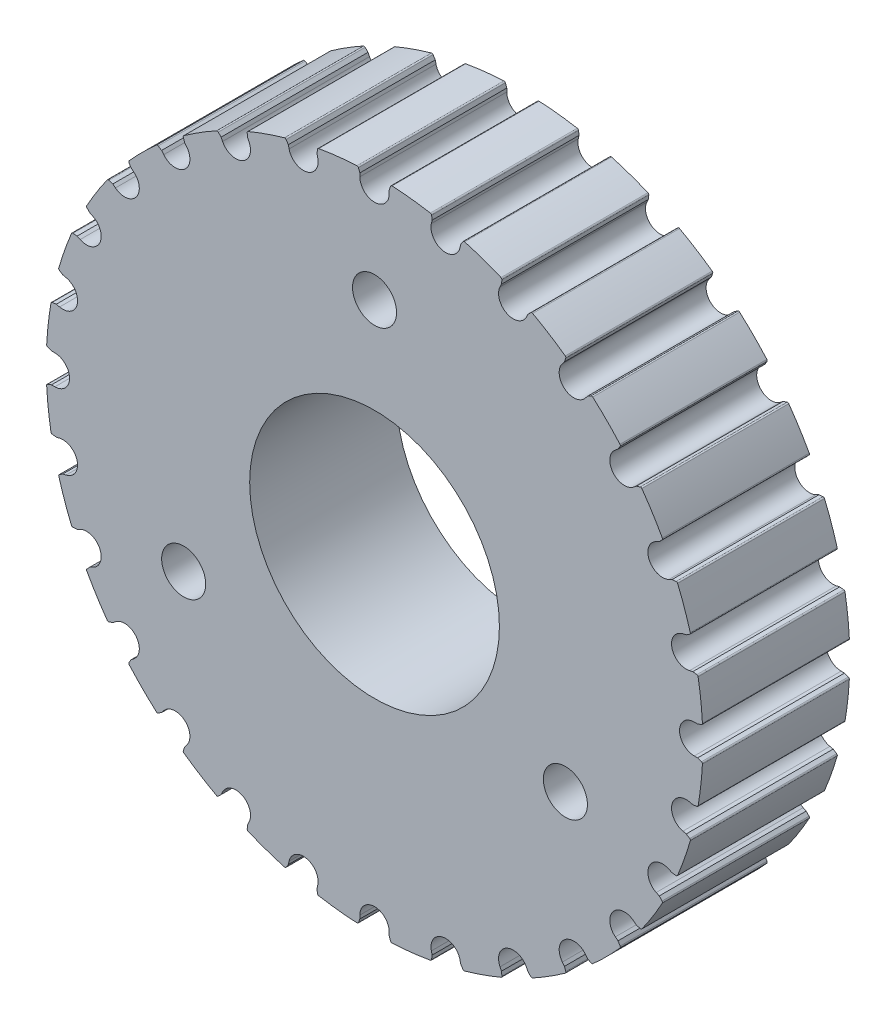
SolidWorks part; units mm, degrees
ref_plane "Спереди" through (0, 0, 0) normal (0, 0, 1) x (1, 0, 0)
ref_plane "Сверху" through (0, 0, 0) normal (0, 1, 0) x (1, 0, 0)
ref_plane "Справа" through (0, 0, 0) normal (1, 0, 0) x (0, 0, -1)
sketch "Эскиз1" plane through (0, 0, 0) normal (0, 0, 1) x (1, 0, 0)
  line L0 (0, 0) -> (0, 13.132) construction
  line L1 (-0.676, 21.1) -> (0, 21.1)
  line L2 (0, 21.1) -> (0.676, 21.1)
  line L3 (-0.676, 21.1) -> (-1.1207, 22.3219)
  line L4 (4.0361, 20.7214) -> (4.6952, 20.571)
  line L5 (4.6952, 20.571) -> (5.3542, 20.4206)
  line L6 (1.1207, 22.3219) -> (0.676, 21.1)
  line L7 (4.0361, 20.7214) -> (3.8745, 22.0116)
  line L8 (6.0597, 21.5128) -> (5.3542, 20.4206)
  line L9 (8.5459, 19.3037) -> (9.1549, 19.0104)
  line L10 (9.1549, 19.0104) -> (9.764, 18.7171)
  line L11 (8.5459, 19.3037) -> (8.6754, 20.5976)
  line L12 (10.6948, 19.6251) -> (9.764, 18.7171)
  line L13 (12.6271, 16.9181) -> (13.1556, 16.4966)
  line L14 (13.1556, 16.4966) -> (13.6842, 16.0752)
  line L15 (12.6271, 16.9181) -> (13.0412, 18.1507)
  line L16 (14.7937, 16.7532) -> (13.6842, 16.0752)
  line L17 (16.0752, 13.6842) -> (16.4966, 13.1556)
  line L18 (16.4966, 13.1556) -> (16.9181, 12.6271)
  line L19 (16.0752, 13.6842) -> (16.7532, 14.7937)
  line L20 (18.1507, 13.0412) -> (16.9181, 12.6271)
  line L21 (18.7171, 9.764) -> (19.0104, 9.1549)
  line L22 (19.0104, 9.1549) -> (19.3037, 8.5459)
  line L23 (18.7171, 9.764) -> (19.6251, 10.6948)
  line L24 (20.5976, 8.6754) -> (19.3037, 8.5459)
  line L25 (20.4206, 5.3542) -> (20.571, 4.6952)
  line L26 (20.571, 4.6952) -> (20.7214, 4.0361)
  line L27 (20.4206, 5.3542) -> (21.5128, 6.0597)
  line L28 (22.0116, 3.8745) -> (20.7214, 4.0361)
  line L29 (21.1, 0.676) -> (21.1, 0)
  line L30 (21.1, 0) -> (21.1, -0.676)
  line L31 (21.1, 0.676) -> (22.3219, 1.1207)
  line L32 (22.3219, -1.1207) -> (21.1, -0.676)
  line L33 (20.7214, -4.0361) -> (20.571, -4.6952)
  line L34 (20.571, -4.6952) -> (20.4206, -5.3542)
  line L35 (20.7214, -4.0361) -> (22.0116, -3.8745)
  line L36 (21.5128, -6.0597) -> (20.4206, -5.3542)
  line L37 (19.3037, -8.5459) -> (19.0104, -9.1549)
  line L38 (19.0104, -9.1549) -> (18.7171, -9.764)
  line L39 (19.3037, -8.5459) -> (20.5976, -8.6754)
  line L40 (19.6251, -10.6948) -> (18.7171, -9.764)
  line L41 (16.9181, -12.6271) -> (16.4966, -13.1556)
  line L42 (16.4966, -13.1556) -> (16.0752, -13.6842)
  line L43 (16.9181, -12.6271) -> (18.1507, -13.0412)
  line L44 (16.7532, -14.7937) -> (16.0752, -13.6842)
  line L45 (13.6842, -16.0752) -> (13.1556, -16.4966)
  line L46 (13.1556, -16.4966) -> (12.6271, -16.9181)
  line L47 (13.6842, -16.0752) -> (14.7937, -16.7532)
  line L48 (13.0412, -18.1507) -> (12.6271, -16.9181)
  line L49 (9.764, -18.7171) -> (9.1549, -19.0104)
  line L50 (9.1549, -19.0104) -> (8.5459, -19.3037)
  line L51 (9.764, -18.7171) -> (10.6948, -19.6251)
  line L52 (8.6754, -20.5976) -> (8.5459, -19.3037)
  line L53 (5.3542, -20.4206) -> (4.6952, -20.571)
  line L54 (4.6952, -20.571) -> (4.0361, -20.7214)
  line L55 (5.3542, -20.4206) -> (6.0597, -21.5128)
  line L56 (3.8745, -22.0116) -> (4.0361, -20.7214)
  line L57 (0.676, -21.1) -> (0, -21.1)
  line L58 (0, -21.1) -> (-0.676, -21.1)
  line L59 (0.676, -21.1) -> (1.1207, -22.3219)
  line L60 (-1.1207, -22.3219) -> (-0.676, -21.1)
  line L61 (-4.0361, -20.7214) -> (-4.6952, -20.571)
  line L62 (-4.6952, -20.571) -> (-5.3542, -20.4206)
  line L63 (-4.0361, -20.7214) -> (-3.8745, -22.0116)
  line L64 (-6.0597, -21.5128) -> (-5.3542, -20.4206)
  line L65 (-8.5459, -19.3037) -> (-9.1549, -19.0104)
  line L66 (-9.1549, -19.0104) -> (-9.764, -18.7171)
  line L67 (-8.5459, -19.3037) -> (-8.6754, -20.5976)
  line L68 (-10.6948, -19.6251) -> (-9.764, -18.7171)
  line L69 (-12.6271, -16.9181) -> (-13.1556, -16.4966)
  line L70 (-13.1556, -16.4966) -> (-13.6842, -16.0752)
  line L71 (-12.6271, -16.9181) -> (-13.0412, -18.1507)
  line L72 (-14.7937, -16.7532) -> (-13.6842, -16.0752)
  line L73 (-16.0752, -13.6842) -> (-16.4966, -13.1556)
  line L74 (-16.4966, -13.1556) -> (-16.9181, -12.6271)
  line L75 (-16.0752, -13.6842) -> (-16.7532, -14.7937)
  line L76 (-18.1507, -13.0412) -> (-16.9181, -12.6271)
  line L77 (-18.7171, -9.764) -> (-19.0104, -9.1549)
  line L78 (-19.0104, -9.1549) -> (-19.3037, -8.5459)
  line L79 (-18.7171, -9.764) -> (-19.6251, -10.6948)
  line L80 (-20.5976, -8.6754) -> (-19.3037, -8.5459)
  line L81 (-20.4206, -5.3542) -> (-20.571, -4.6952)
  line L82 (-20.571, -4.6952) -> (-20.7214, -4.0361)
  line L83 (-20.4206, -5.3542) -> (-21.5128, -6.0597)
  line L84 (-22.0116, -3.8745) -> (-20.7214, -4.0361)
  line L85 (-21.1, -0.676) -> (-21.1, 0)
  line L86 (-21.1, 0) -> (-21.1, 0.676)
  line L87 (-21.1, -0.676) -> (-22.3219, -1.1207)
  line L88 (-22.3219, 1.1207) -> (-21.1, 0.676)
  line L89 (-20.7214, 4.0361) -> (-20.571, 4.6952)
  line L90 (-20.571, 4.6952) -> (-20.4206, 5.3542)
  line L91 (-20.7214, 4.0361) -> (-22.0116, 3.8745)
  line L92 (-21.5128, 6.0597) -> (-20.4206, 5.3542)
  line L93 (-19.3037, 8.5459) -> (-19.0104, 9.1549)
  line L94 (-19.0104, 9.1549) -> (-18.7171, 9.764)
  line L95 (-19.3037, 8.5459) -> (-20.5976, 8.6754)
  line L96 (-19.6251, 10.6948) -> (-18.7171, 9.764)
  line L97 (-16.9181, 12.6271) -> (-16.4966, 13.1556)
  line L98 (-16.4966, 13.1556) -> (-16.0752, 13.6842)
  line L99 (-16.9181, 12.6271) -> (-18.1507, 13.0412)
  line L100 (-16.7532, 14.7937) -> (-16.0752, 13.6842)
  line L101 (-13.6842, 16.0752) -> (-13.1556, 16.4966)
  line L102 (-13.1556, 16.4966) -> (-12.6271, 16.9181)
  line L103 (-13.6842, 16.0752) -> (-14.7937, 16.7532)
  line L104 (-13.0412, 18.1507) -> (-12.6271, 16.9181)
  line L105 (-9.764, 18.7171) -> (-9.1549, 19.0104)
  line L106 (-9.1549, 19.0104) -> (-8.5459, 19.3037)
  line L107 (-9.764, 18.7171) -> (-10.6948, 19.6251)
  line L108 (-8.6754, 20.5976) -> (-8.5459, 19.3037)
  line L109 (-5.3542, 20.4206) -> (-4.6952, 20.571)
  line L110 (-4.6952, 20.571) -> (-4.0361, 20.7214)
  line L111 (-5.3542, 20.4206) -> (-6.0597, 21.5128)
  line L112 (-3.8745, 22.0116) -> (-4.0361, 20.7214)
  line L114 (0, 21.1) -> (0, 22.3219) construction
  arc A0 (-1.1207, 22.3219) -> (-3.8745, 22.0116) centre (0, 0) ccw
  arc A1 (-6.0597, 21.5128) -> (-8.6754, 20.5976) centre (0, 0) ccw
  arc A2 (-10.6948, 19.6251) -> (-13.0412, 18.1507) centre (0, 0) ccw
  arc A3 (-14.7937, 16.7532) -> (-16.7532, 14.7937) centre (0, 0) ccw
  arc A4 (-18.1507, 13.0412) -> (-19.6251, 10.6948) centre (0, 0) ccw
  arc A5 (-20.5976, 8.6754) -> (-21.5128, 6.0597) centre (0, 0) ccw
  arc A6 (-22.0116, 3.8745) -> (-22.3219, 1.1207) centre (0, 0) ccw
  arc A7 (-22.3219, -1.1207) -> (-22.0116, -3.8745) centre (0, 0) ccw
  arc A8 (-21.5128, -6.0597) -> (-20.5976, -8.6754) centre (0, 0) ccw
  arc A9 (-19.6251, -10.6948) -> (-18.1507, -13.0412) centre (0, 0) ccw
  arc A10 (-16.7532, -14.7937) -> (-14.7937, -16.7532) centre (0, 0) ccw
  arc A11 (-13.0412, -18.1507) -> (-10.6948, -19.6251) centre (0, 0) ccw
  arc A12 (-8.6754, -20.5976) -> (-6.0597, -21.5128) centre (0, 0) ccw
  arc A13 (-3.8745, -22.0116) -> (-1.1207, -22.3219) centre (0, 0) ccw
  arc A14 (1.1207, -22.3219) -> (3.8745, -22.0116) centre (0, 0) ccw
  arc A15 (6.0597, -21.5128) -> (8.6754, -20.5976) centre (0, 0) ccw
  arc A16 (10.6948, -19.6251) -> (13.0412, -18.1507) centre (0, 0) ccw
  arc A17 (14.7937, -16.7532) -> (16.7532, -14.7937) centre (0, 0) ccw
  arc A18 (18.1507, -13.0412) -> (19.6251, -10.6948) centre (0, 0) ccw
  arc A19 (20.5976, -8.6754) -> (21.5128, -6.0597) centre (0, 0) ccw
  arc A20 (22.0116, -3.8745) -> (22.3219, -1.1207) centre (0, 0) ccw
  arc A21 (22.3219, 1.1207) -> (22.0116, 3.8745) centre (0, 0) ccw
  arc A22 (21.5128, 6.0597) -> (20.5976, 8.6754) centre (0, 0) ccw
  arc A23 (19.6251, 10.6948) -> (18.1507, 13.0412) centre (0, 0) ccw
  arc A24 (16.7532, 14.7937) -> (14.7937, 16.7532) centre (0, 0) ccw
  arc A25 (13.0412, 18.1507) -> (10.6948, 19.6251) centre (0, 0) ccw
  arc A26 (8.6754, 20.5976) -> (6.0597, 21.5128) centre (0, 0) ccw
  arc A27 (3.8745, 22.0116) -> (1.1207, 22.3219) centre (0, 0) ccw
  circle A28 centre (0, 0) radius 8.5
  dimension "D1" = 44.7
  dimension "D2" = 0.676
  dimension "D4" = 40
  dimension "D6" = 17
  dimension "D3" = 0.676
  dimension "D5" = 110
extrude "Вытянуть1" add sketch "Эскиз1" along normal blind 10
fillet "Скругление1" radius 0.1 83 edges at (12.6271, 16.9181, 5) (13.0412, 18.1507, 5) (10.6948, 19.6251, 5) (9.764, 18.7171, 5) (8.5459, 19.3037, 5) (8.6754, 20.5976, 5) (5.3542, 20.4206, 5) (6.0597, 21.5128, 5) (4.0361, 20.7214, 5) (3.8745, 22.0116, 5) (1.1207, 22.3219, 5) (0.676, 21.1, 5) (-0.676, 21.1, 5) (-1.1207, 22.3219, 5) (-3.8745, 22.0116, 5) (-4.0361, 20.7214, 5) (-5.3542, 20.4206, 5) (-6.0597, 21.5128, 5) (-8.5459, 19.3037, 5) (-8.6754, 20.5976, 5) (-9.764, 18.7171, 5) (-16.0752, -13.6842, 5) (-16.7532, -14.7937, 5) (-18.7171, -9.764, 5) (-19.6251, -10.6948, 5) (-21.5128, -6.0597, 5) (-20.4206, -5.3542, 5) (-22.3219, -1.1207, 5) (-21.1, -0.676, 5) (-22.0116, 3.8745, 5) (-20.7214, 4.0361, 5) (-20.5976, 8.6754, 5) (-19.3037, 8.5459, 5) (-18.1507, 13.0412, 5) (-16.9181, 12.6271, 5) (-10.6948, 19.6251, 5) (-13.0412, 18.1507, 5) (-12.6271, 16.9181, 5) (-14.7937, 16.7532, 5) (-16.7532, 14.7937, 5) (-16.0752, 13.6842, 5) (-19.6251, 10.6948, 5) (-18.7171, 9.764, 5) (-21.5128, 6.0597, 5) (-20.4206, 5.3542, 5) (-22.3219, 1.1207, 5) (-21.1, 0.676, 5) (-22.0116, -3.8745, 5) (-20.7214, -4.0361, 5) (-20.5976, -8.6754, 5) (-19.3037, -8.5459, 5) (-18.1507, -13.0412, 5) (-16.9181, -12.6271, 5) (-14.7937, -16.7532, 5) (-13.6842, -16.0752, 5) (-10.6948, -19.6251, 5) (-9.764, -18.7171, 5) (-6.0597, -21.5128, 5) (-5.3542, -20.4206, 5) (-1.1207, -22.3219, 5) (-0.676, -21.1, 5) (3.8745, -22.0116, 5) (4.0361, -20.7214, 5) (8.6754, -20.5976, 5) (8.5459, -19.3037, 5) (13.0412, -18.1507, 5) (12.6271, -16.9181, 5) (16.7532, -14.7937, 5) (16.0752, -13.6842, 5) (19.6251, -10.6948, 5) (18.7171, -9.764, 5) (21.5128, -6.0597, 5) (20.4206, -5.3542, 5) (22.3219, -1.1207, 5) (21.1, -0.676, 5) (22.0116, 3.8745, 5) (20.7214, 4.0361, 5) (20.5976, 8.6754, 5) (19.3037, 8.5459, 5) (18.1507, 13.0412, 5) (16.9181, 12.6271, 5) (14.7937, 16.7532, 5) (13.6842, 16.0752, 5)
fillet "Скругление2" radius 0.1 28 edges at (-12.6271, -16.9181, 5) (-13.0412, -18.1507, 5) (-8.5459, -19.3037, 5) (-8.6754, -20.5976, 5) (-4.0361, -20.7214, 5) (-3.8745, -22.0116, 5) (0.676, -21.1, 5) (1.1207, -22.3219, 5) (5.3542, -20.4206, 5) (6.0597, -21.5128, 5) (9.764, -18.7171, 5) (10.6948, -19.6251, 5) (13.6842, -16.0752, 5) (14.7937, -16.7532, 5) (16.9181, -12.6271, 5) (18.1507, -13.0412, 5) (19.3037, -8.5459, 5) (20.5976, -8.6754, 5) (20.7214, -4.0361, 5) (22.0116, -3.8745, 5) (21.1, 0.676, 5) (22.3219, 1.1207, 5) (20.4206, 5.3542, 5) (21.5128, 6.0597, 5) (18.7171, 9.764, 5) (19.6251, 10.6948, 5) (16.0752, 13.6842, 5) (16.7532, 14.7937, 5)
sketch "Эскиз2" plane through (0, 0, 10) normal (0, 0, 1) x (1, 0, 0)
  line L0 (0, 0) -> (0, 24.0067) construction
  line L1 (6.0815, 22.1509) -> (5.817, 20.992)
  line L2 (-1, 22.9488) -> (1, 22.9488)
  line L3 (-1, 22.9488) -> (-1, 21.7601)
  line L4 (4.1317, 22.5959) -> (6.0815, 22.1509)
  line L5 (1, 22.9488) -> (1, 21.7601)
  line L6 (4.1317, 22.5959) -> (3.8672, 21.4371)
  line L7 (10.8581, 20.2422) -> (10.3423, 19.1713)
  line L8 (9.0561, 21.11) -> (10.8581, 20.2422)
  line L9 (9.0561, 21.11) -> (8.5404, 20.0391)
  line L10 (15.0901, 17.3186) -> (14.349, 16.3893)
  line L11 (13.5265, 18.5655) -> (15.0901, 17.3186)
  line L12 (13.5265, 18.5655) -> (12.7854, 17.6362)
  line L13 (18.5655, 13.5265) -> (17.6362, 12.7854)
  line L14 (17.3186, 15.0901) -> (18.5655, 13.5265)
  line L15 (17.3186, 15.0901) -> (16.3893, 14.349)
  line L16 (21.11, 9.0561) -> (20.0391, 8.5404)
  line L17 (20.2422, 10.8581) -> (21.11, 9.0561)
  line L18 (20.2422, 10.8581) -> (19.1713, 10.3423)
  line L19 (22.5959, 4.1317) -> (21.4371, 3.8672)
  line L20 (22.1509, 6.0815) -> (22.5959, 4.1317)
  line L21 (22.1509, 6.0815) -> (20.992, 5.817)
  line L22 (22.9488, -1) -> (21.7601, -1)
  line L23 (22.9488, 1) -> (22.9488, -1)
  line L24 (22.9488, 1) -> (21.7601, 1)
  line L25 (22.1509, -6.0815) -> (20.992, -5.817)
  line L26 (22.5959, -4.1317) -> (22.1509, -6.0815)
  line L27 (22.5959, -4.1317) -> (21.4371, -3.8672)
  line L28 (20.2422, -10.8581) -> (19.1713, -10.3423)
  line L29 (21.11, -9.0561) -> (20.2422, -10.8581)
  line L30 (21.11, -9.0561) -> (20.0391, -8.5404)
  line L31 (17.3186, -15.0901) -> (16.3893, -14.349)
  line L32 (18.5655, -13.5265) -> (17.3186, -15.0901)
  line L33 (18.5655, -13.5265) -> (17.6362, -12.7854)
  line L34 (13.5265, -18.5655) -> (12.7854, -17.6362)
  line L35 (15.0901, -17.3186) -> (13.5265, -18.5655)
  line L36 (15.0901, -17.3186) -> (14.349, -16.3893)
  line L37 (9.0561, -21.11) -> (8.5404, -20.0391)
  line L38 (10.8581, -20.2422) -> (9.0561, -21.11)
  line L39 (10.8581, -20.2422) -> (10.3423, -19.1713)
  line L40 (4.1317, -22.5959) -> (3.8672, -21.4371)
  line L41 (6.0815, -22.1509) -> (4.1317, -22.5959)
  line L42 (6.0815, -22.1509) -> (5.817, -20.992)
  line L43 (-1, -22.9488) -> (-1, -21.7601)
  line L44 (1, -22.9488) -> (-1, -22.9488)
  line L45 (1, -22.9488) -> (1, -21.7601)
  line L46 (-6.0815, -22.1509) -> (-5.817, -20.992)
  line L47 (-4.1317, -22.5959) -> (-6.0815, -22.1509)
  line L48 (-4.1317, -22.5959) -> (-3.8672, -21.4371)
  line L49 (-10.8581, -20.2422) -> (-10.3423, -19.1713)
  line L50 (-9.0561, -21.11) -> (-10.8581, -20.2422)
  line L51 (-9.0561, -21.11) -> (-8.5404, -20.0391)
  line L52 (-15.0901, -17.3186) -> (-14.349, -16.3893)
  line L53 (-13.5265, -18.5655) -> (-15.0901, -17.3186)
  line L54 (-13.5265, -18.5655) -> (-12.7854, -17.6362)
  line L55 (-18.5655, -13.5265) -> (-17.6362, -12.7854)
  line L56 (-17.3186, -15.0901) -> (-18.5655, -13.5265)
  line L57 (-17.3186, -15.0901) -> (-16.3893, -14.349)
  line L58 (-21.11, -9.0561) -> (-20.0391, -8.5404)
  line L59 (-20.2422, -10.8581) -> (-21.11, -9.0561)
  line L60 (-20.2422, -10.8581) -> (-19.1713, -10.3423)
  line L61 (-22.5959, -4.1317) -> (-21.4371, -3.8672)
  line L62 (-22.1509, -6.0815) -> (-22.5959, -4.1317)
  line L63 (-22.1509, -6.0815) -> (-20.992, -5.817)
  line L64 (-22.9488, 1) -> (-21.7601, 1)
  line L65 (-22.9488, -1) -> (-22.9488, 1)
  line L66 (-22.9488, -1) -> (-21.7601, -1)
  line L67 (-22.1509, 6.0815) -> (-20.992, 5.817)
  line L68 (-22.5959, 4.1317) -> (-22.1509, 6.0815)
  line L69 (-22.5959, 4.1317) -> (-21.4371, 3.8672)
  line L70 (-20.2422, 10.8581) -> (-19.1713, 10.3423)
  line L71 (-21.11, 9.0561) -> (-20.2422, 10.8581)
  line L72 (-21.11, 9.0561) -> (-20.0391, 8.5404)
  line L73 (-17.3186, 15.0901) -> (-16.3893, 14.349)
  line L74 (-18.5655, 13.5265) -> (-17.3186, 15.0901)
  line L75 (-18.5655, 13.5265) -> (-17.6362, 12.7854)
  line L76 (-13.5265, 18.5655) -> (-12.7854, 17.6362)
  line L77 (-15.0901, 17.3186) -> (-13.5265, 18.5655)
  line L78 (-15.0901, 17.3186) -> (-14.349, 16.3893)
  line L79 (-9.0561, 21.11) -> (-8.5404, 20.0391)
  line L80 (-10.8581, 20.2422) -> (-9.0561, 21.11)
  line L81 (-10.8581, 20.2422) -> (-10.3423, 19.1713)
  line L82 (-4.1317, 22.5959) -> (-3.8672, 21.4371)
  line L83 (-6.0815, 22.1509) -> (-4.1317, 22.5959)
  line L84 (-6.0815, 22.1509) -> (-5.817, 20.992)
  arc A0 (-1, 21.7601) -> (1, 21.7601) centre (0, 21.7601) ccw
  arc A1 (3.8672, 21.4371) -> (5.817, 20.992) centre (4.8421, 21.2145) ccw
  arc A2 (8.5404, 20.0391) -> (10.3423, 19.1713) centre (9.4414, 19.6052) ccw
  arc A3 (12.7854, 17.6362) -> (14.349, 16.3893) centre (13.5672, 17.0127) ccw
  arc A4 (16.3893, 14.349) -> (17.6362, 12.7854) centre (17.0127, 13.5672) ccw
  arc A5 (19.1713, 10.3423) -> (20.0391, 8.5404) centre (19.6052, 9.4414) ccw
  arc A6 (20.992, 5.817) -> (21.4371, 3.8672) centre (21.2145, 4.8421) ccw
  arc A7 (21.7601, 1) -> (21.7601, -1) centre (21.7601, 0) ccw
  arc A8 (21.4371, -3.8672) -> (20.992, -5.817) centre (21.2145, -4.8421) ccw
  arc A9 (20.0391, -8.5404) -> (19.1713, -10.3423) centre (19.6052, -9.4414) ccw
  arc A10 (17.6362, -12.7854) -> (16.3893, -14.349) centre (17.0127, -13.5672) ccw
  arc A11 (14.349, -16.3893) -> (12.7854, -17.6362) centre (13.5672, -17.0127) ccw
  arc A12 (10.3423, -19.1713) -> (8.5404, -20.0391) centre (9.4414, -19.6052) ccw
  arc A13 (5.817, -20.992) -> (3.8672, -21.4371) centre (4.8421, -21.2145) ccw
  arc A14 (1, -21.7601) -> (-1, -21.7601) centre (0, -21.7601) ccw
  arc A15 (-3.8672, -21.4371) -> (-5.817, -20.992) centre (-4.8421, -21.2145) ccw
  arc A16 (-8.5404, -20.0391) -> (-10.3423, -19.1713) centre (-9.4414, -19.6052) ccw
  arc A17 (-12.7854, -17.6362) -> (-14.349, -16.3893) centre (-13.5672, -17.0127) ccw
  arc A18 (-16.3893, -14.349) -> (-17.6362, -12.7854) centre (-17.0127, -13.5672) ccw
  arc A19 (-19.1713, -10.3423) -> (-20.0391, -8.5404) centre (-19.6052, -9.4414) ccw
  arc A20 (-20.992, -5.817) -> (-21.4371, -3.8672) centre (-21.2145, -4.8421) ccw
  arc A21 (-21.7601, -1) -> (-21.7601, 1) centre (-21.7601, 0) ccw
  arc A22 (-21.4371, 3.8672) -> (-20.992, 5.817) centre (-21.2145, 4.8421) ccw
  arc A23 (-20.0391, 8.5404) -> (-19.1713, 10.3423) centre (-19.6052, 9.4414) ccw
  arc A24 (-17.6362, 12.7854) -> (-16.3893, 14.349) centre (-17.0127, 13.5672) ccw
  arc A25 (-14.349, 16.3893) -> (-12.7854, 17.6362) centre (-13.5672, 17.0127) ccw
  arc A26 (-10.3423, 19.1713) -> (-8.5404, 20.0391) centre (-9.4414, 19.6052) ccw
  arc A27 (-5.817, 20.992) -> (-3.8672, 21.4371) centre (-4.8421, 21.2145) ccw
  dimension "D2" = 1
extrude "Вырез-Вытянуть1" cut sketch "Эскиз2" against normal blind 10
sketch "Эскиз3" plane through (0, 0, 10) normal (0, 0, 1) x (1, 0, 0)
  line L0 (0, 0) -> (0, 15) construction
  circle A0 centre (0, 15) radius 1.5
  circle A1 centre (12.9904, -7.5) radius 1.5
  circle A2 centre (-12.9904, -7.5) radius 1.5
  dimension "D1" = 15
  dimension "D2" = 3
extrude "Вырез-Вытянуть2" cut sketch "Эскиз3" against normal blind 10
